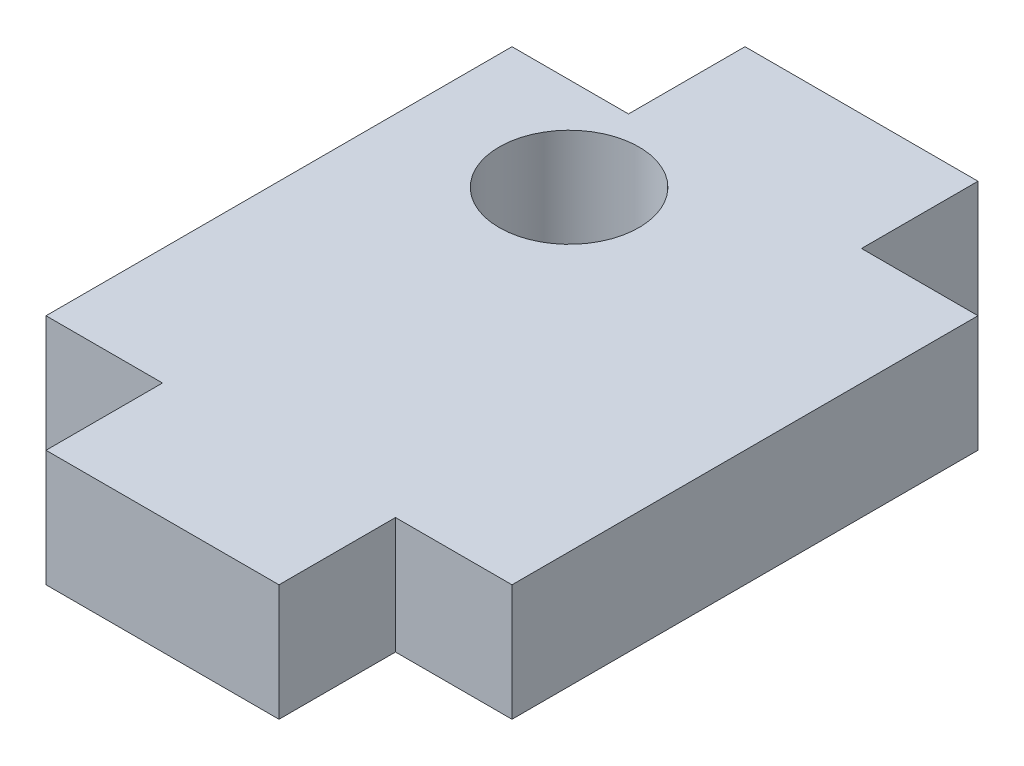
SolidWorks part; units mm, degrees
ref_plane "前视基准面" through (0, 0, 0) normal (0, 0, 1) x (1, 0, 0)
ref_plane "上视基准面" through (0, 0, 0) normal (0, 1, 0) x (1, 0, 0)
ref_plane "右视基准面" through (0, 0, 0) normal (1, 0, 0) x (0, 0, -1)
sketch "草图1" plane through (0, 0, 0) normal (0, 1, 0) x (1, 0, 0)
  line L0 (6.45, 42.4337) -> (6.45, -9.2114) construction
  line L1 (0, 0) -> (5, 0)
  line L2 (0, 0) -> (0, 20)
  line L3 (0, 20) -> (5, 20)
  line L4 (20, 0) -> (20, 20)
  line L5 (15, 0) -> (20, 0)
  line L6 (5, 20) -> (5, 25)
  line L7 (5, 25) -> (15, 25)
  line L8 (15, 20) -> (15, 25)
  line L10 (5, 0) -> (5, -5)
  line L11 (5, -5) -> (15, -5)
  line L12 (15, 0) -> (15, -5)
  line L13 (-6.1531, 16) -> (27.0711, 16) construction
  line L14 (15, 20) -> (20, 20)
  circle A0 centre (6.45, 16) radius 3
  dimension "D1" = 20
  dimension "D2" = 20
  dimension "D3" = 5
  dimension "D4" = 5
  dimension "D5" = 10
  dimension "D6" = 10
  dimension "D7" = 5
  dimension "D8" = 5
  dimension "D9" = 6.45
  dimension "D10" = 4
extrude "凸台-拉伸1" add sketch "草图1" along normal blind 5
